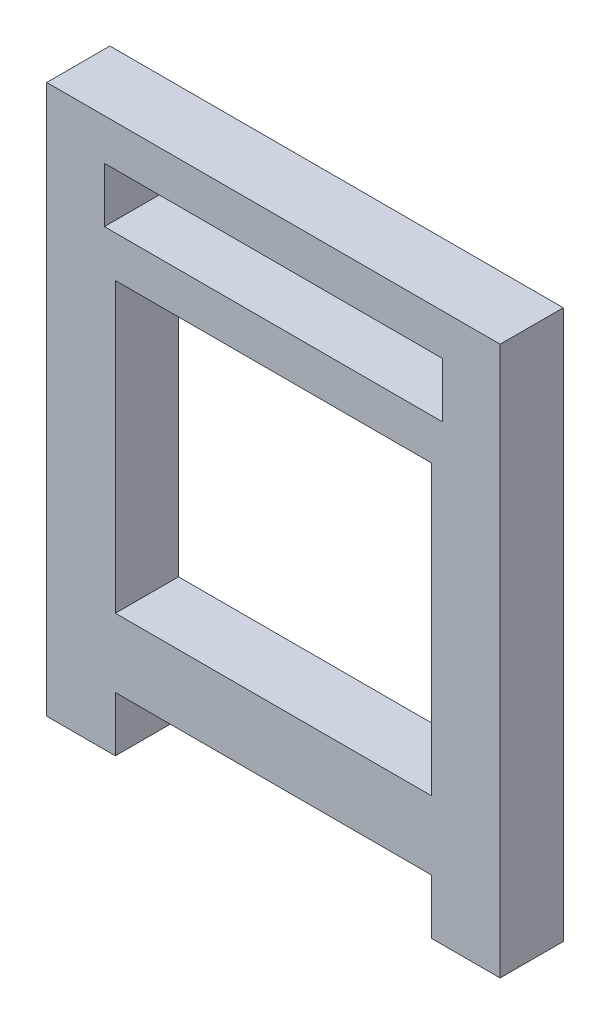
SolidWorks part; units mm, degrees
ref_plane "Front Plane" through (0, 0, 0) normal (0, 0, 1) x (1, 0, 0)
ref_plane "Top Plane" through (0, 0, 0) normal (0, 1, 0) x (1, 0, 0)
ref_plane "Right Plane" through (0, 0, 0) normal (1, 0, 0) x (0, 0, -1)
sketch "Sketch1" plane through (0, 0, 0) normal (0, 0, 1) x (1, 0, 0)
  line L0 (0, 0) -> (0, -2)
  line L1 (2.5, 0) -> (14.02, 0)
  line L2 (0, 0) -> (0, 18)
  line L3 (0, 18) -> (16.52, 18)
  line L4 (16.52, 0) -> (16.52, 18)
  line L5 (0, -2) -> (2.5, -2)
  line L6 (2.5, -2) -> (2.5, 0)
  line L7 (16.52, 0) -> (16.52, -2)
  line L8 (16.52, -2) -> (14.02, -2)
  line L9 (14.02, -2) -> (14.02, 0)
  line L12 (2.5, 2.5) -> (14.02, 2.5)
  line L13 (2.5, 2.5) -> (2.5, 13)
  line L14 (2.5, 13) -> (14.02, 13)
  line L15 (14.02, 2.5) -> (14.02, 13)
  line L16 (2.1, 14.5) -> (14.42, 14.5)
  line L17 (2.1, 14.5) -> (2.1, 16.5)
  line L18 (2.1, 16.5) -> (14.42, 16.5)
  line L19 (14.42, 14.5) -> (14.42, 16.5)
  dimension "D1" = 18
  dimension "D2" = 2.5
  dimension "D3" = 11.52
  dimension "D4" = 2
  dimension "D5" = 2
  dimension "D6" = 2.5
  dimension "D7" = 2.5
  dimension "D8" = 10.5
  dimension "D9" = 2
  dimension "D10" = 1.5
  dimension "D12" = 0.4
extrude "Boss-Extrude1" add sketch "Sketch1" along normal blind 2.3
